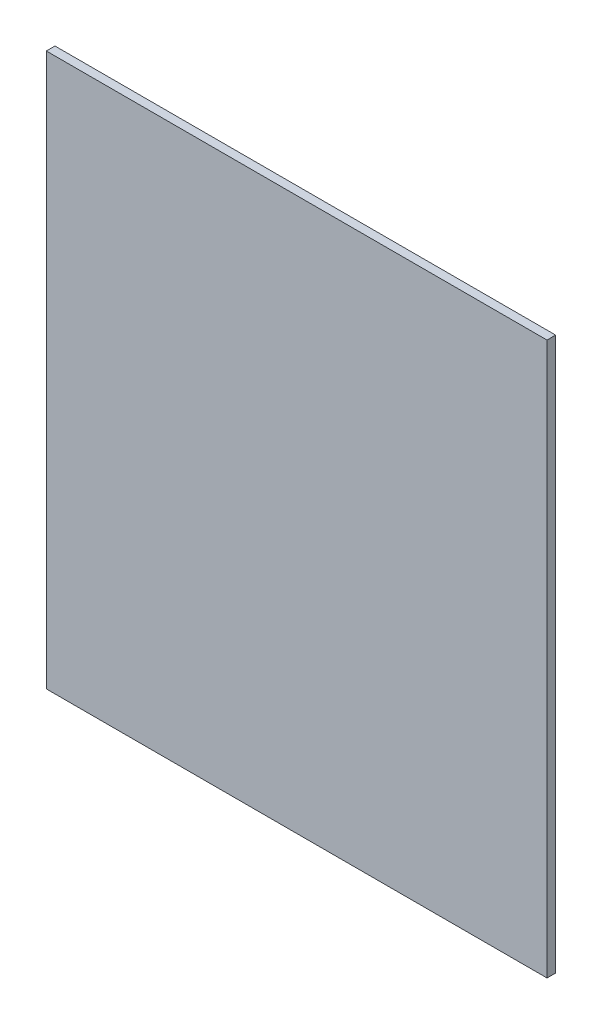
SolidWorks part; units mm, degrees
ref_plane "Plan de face" through (0, 0, 0) normal (0, 0, 1) x (1, 0, 0)
ref_plane "Plan de dessus" through (0, 0, 0) normal (0, 1, 0) x (1, 0, 0)
ref_plane "Plan de droite" through (0, 0, 0) normal (1, 0, 0) x (0, 0, -1)
sketch "Esquisse1" plane through (0, 0, 0) normal (0, 0, 1) x (1, 0, 0)
  line L1 (0, 0) -> (290, 0)
  line L2 (0, 0) -> (0, 320)
  line L3 (0, 320) -> (290, 320)
  line L4 (290, 0) -> (290, 320)
  dimension "D1" = 320
  dimension "D2" = 290
extrude "Boss.-Extru.1" add sketch "Esquisse1" along normal blind 5
